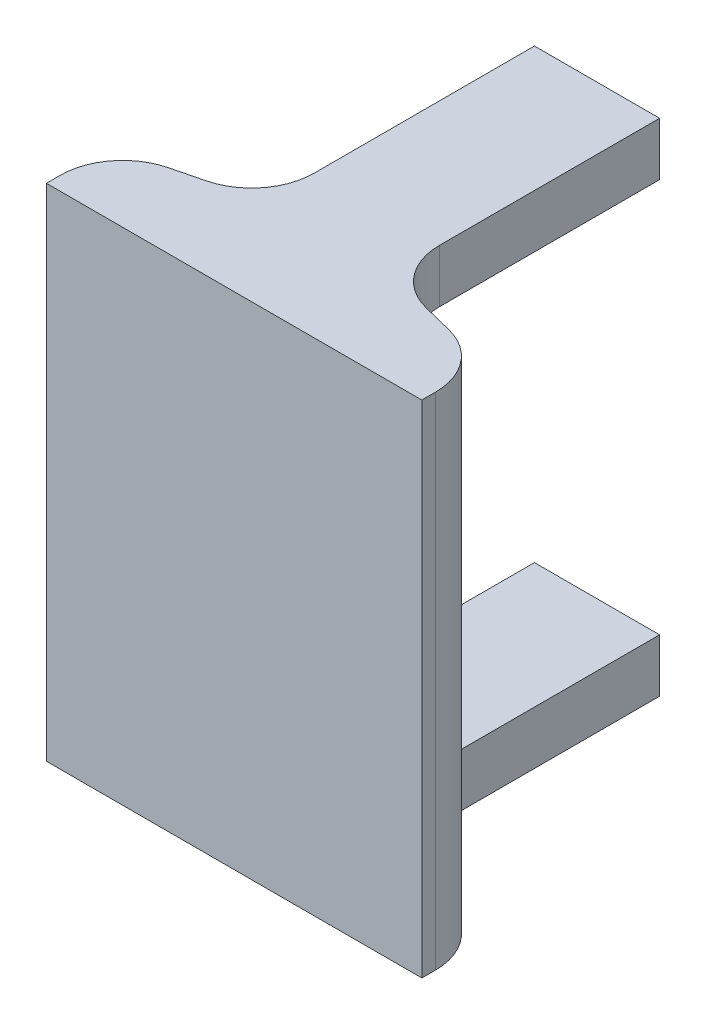
SolidWorks part; units mm, degrees
ref_plane "Front Plane" through (0, 0, 0) normal (0, 0, 1) x (1, 0, 0)
ref_plane "Top Plane" through (0, 0, 0) normal (0, 1, 0) x (1, 0, 0)
ref_plane "Right Plane" through (0, 0, 0) normal (1, 0, 0) x (0, 0, -1)
sketch "Sketch1" plane through (0, 0, 0) normal (0, 1, 0) x (1, 0, 0)
  line L0 (0, 0) -> (0, -15) construction
  line L1 (0, -15) -> (-30, -15)
  line L2 (0, -15) -> (30, -15)
  line L3 (0, 43) -> (10, 43)
  line L4 (0, 0) -> (0, 43) construction
  line L5 (0, 43) -> (-10, 43)
  line L6 (-10, 43) -> (-10, 7.8078)
  line L7 (-30, -15) -> (-30, -12.8078)
  line L8 (-22.4254, -3.1063) -> (-17.5746, -1.8937)
  line L9 (10, 43) -> (10, 7.8078)
  line L10 (30, -15) -> (30, -12.8078)
  line L11 (22.4254, -3.1063) -> (17.5746, -1.8937)
  arc A0 (-10, 7.8078) -> (-17.5746, -1.8937) centre (-20, 7.8078) cw
  arc A1 (10, 7.8078) -> (17.5746, -1.8937) centre (20, 7.8078) ccw
  arc A2 (30, -12.8078) -> (22.4254, -3.1063) centre (20, -12.8078) ccw
  arc A3 (-30, -12.8078) -> (-22.4254, -3.1063) centre (-20, -12.8078) cw
  point P15 (-10, 25)
  point P22 (-30, -5)
  dimension "D9" = 10
  dimension "D1" = 15
  dimension "D2" = 30
  dimension "D3" = 30
  dimension "D4" = 43
  dimension "D5" = 10
  dimension "D6" = 10
  dimension "D7" = 10
  dimension "D8" = 18
extrude "Boss-Extrude1" add sketch "Sketch1" along normal blind 80
sketch "Sketch2" plane through (0, 0, 0) normal (1, 0, 0) x (0, 0, -1)
  line L0 (25.4039, 80) -> (25.4039, 71.5) construction
  line L1 (7.8078, 80) -> (43, 80) construction
  line L2 (25.4039, 0) -> (25.4039, 8.5) construction
  line L3 (7.8078, 0) -> (43, 0) construction
  line L4 (-15, 71.5) -> (3, 71.5) construction
  line L5 (-15, 80) -> (-15, 0) construction
  line L6 (3, 71.5) -> (43, 71.5)
  line L7 (43, 80) -> (43, 0) construction
  line L8 (3, 71.5) -> (3, 8.5)
  line L9 (3, 8.5) -> (43, 8.5)
  dimension "D1" = 8.5
  dimension "D2" = 8.5
  dimension "D3" = 18
extrude "Cut-Extrude1" cut sketch "Sketch2" against normal through all both and the other way through all
